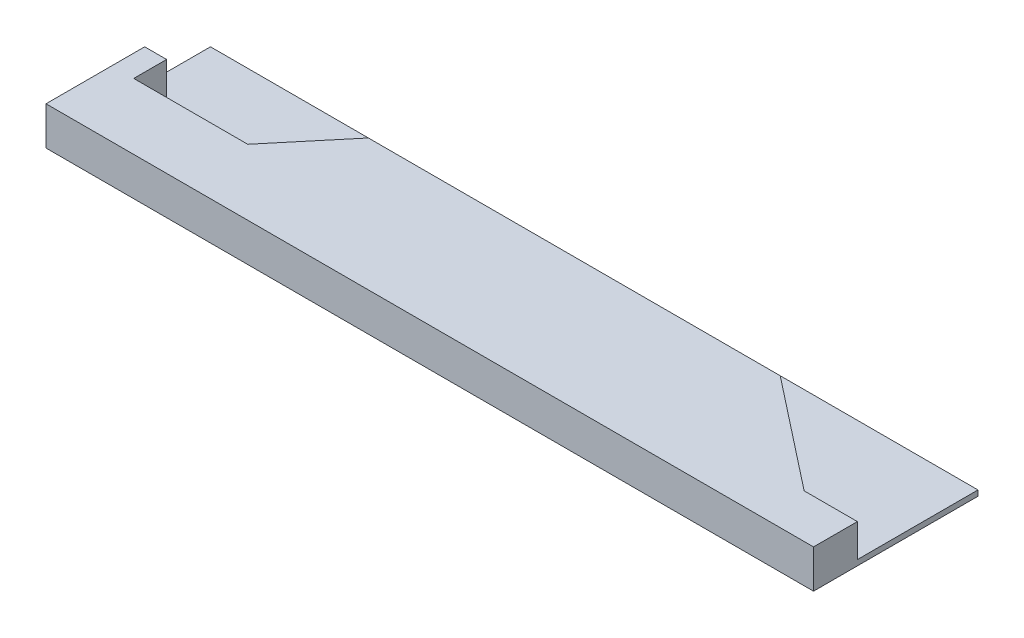
SolidWorks part; units mm, degrees
ref_plane "Front Plane" through (0, 0, 0) normal (0, 0, 1) x (1, 0, 0)
ref_plane "Top Plane" through (0, 0, 0) normal (0, 1, 0) x (1, 0, 0)
ref_plane "Right Plane" through (0, 0, 0) normal (1, 0, 0) x (0, 0, -1)
sketch "Sketch1" plane through (0, 0, 0) normal (0, 1, 0) x (1, 0, 0)
  line L0 (0, 19.05) -> (0, 57.15)
  line L1 (0, 0) -> (57.15, 0)
  line L2 (0, 0) -> (0, 19.05)
  line L3 (0, 19.05) -> (57.15, 19.05)
  line L4 (57.15, 0) -> (57.15, 19.05)
  line L5 (0, 57.15) -> (88.9, 57.15)
  line L6 (88.9, 57.15) -> (57.15, 19.05)
  line L7 (88.9, 57.15) -> (342.9, 57.15)
  line L8 (342.9, 57.15) -> (431.8, -12.7)
  line L9 (342.9, 57.15) -> (88.9, 57.15)
  line L10 (342.9, 57.15) -> (342.9, 38.1)
  line L11 (342.9, 38.1) -> (88.9, 38.1)
  line L12 (88.9, 57.15) -> (88.9, 38.1)
  line L13 (342.9, 57.15) -> (431.8, 57.15)
  line L14 (342.9, 57.15) -> (342.9, -12.7)
  line L15 (342.9, -12.7) -> (431.8, -12.7)
  line L16 (431.8, 57.15) -> (431.8, -12.7)
  line L17 (431.8, -12.7) -> (420.0305, -27.6794)
  line L18 (420.0305, -27.6794) -> (336.3113, 38.1)
  line L19 (57.15, 19.05) -> (73.025, 38.1)
  line L20 (57.15, 19.05) -> (71.1524, 6.1336)
  line L21 (71.1524, 6.1336) -> (103.8794, 45.3805)
  line L22 (57.15, 0) -> (66.0378, 0)
  line L23 (88.9, 57.15) -> (103.8794, 45.3805)
  line L24 (73.025, 38.1) -> (87.6596, 25.9045)
  line L25 (71.1524, 6.1336) -> (64.1512, -2.2625)
extrude "Boss-Extrude1" add sketch "Sketch1" along normal blind 19.05
sketch "Sketch2" plane through (0, 0, 0) normal (0, 0, 1) x (1, 0, 0)
  line L0 (0, 9.525) -> (8.89, 9.525)
  line L1 (0, 19.05) -> (0, 0) construction
  line L2 (0, 9.525) -> (56.515, 9.525)
  circle A0 centre (8.89, 9.525) radius 3.9688
  circle A1 centre (56.515, 9.525) radius 3.9687
extrude "Cut-Extrude1" cut sketch "Sketch2" against normal blind 19.05
sketch "Sketch3" plane through (0, 0, 0) normal (0, -1, 0) x (1, 0, 0)
  line L0 (0, -19.05) -> (0, 0)
  line L1 (0, 0) -> (66.0378, 0)
  line L2 (66.0378, 0) -> (97.8084, -38.1)
  line L3 (97.8084, -38.1) -> (336.3113, -38.1)
  line L4 (336.3113, -38.1) -> (400.9659, 12.7)
  line L5 (400.9659, 12.7) -> (431.8, 12.7)
  line L6 (431.8, 12.7) -> (342.9, -57.15)
  line L7 (342.9, -57.15) -> (88.9, -57.15)
  line L8 (88.9, -57.15) -> (57.15, -19.05)
  line L9 (57.15, -19.05) -> (0, -19.05)
  line L10 (0, -19.05) -> (-12.7, -19.05)
  line L11 (-12.7, -19.05) -> (-12.7, -114.3)
  line L12 (431.8, 12.7) -> (431.8, 38.1)
  line L13 (431.8, 38.1) -> (444.5, 38.1)
  line L15 (-12.7, -114.3) -> (444.5, -114.3)
  line L16 (-12.7, -114.3) -> (-12.7, 38.1)
  line L17 (-12.7, 38.1) -> (444.5, 38.1)
  line L18 (444.5, -114.3) -> (444.5, 38.1)
extrude "Boss-Extrude3" add sketch "Sketch3" along normal blind 19.05 separate body contours L15 L18 L13 L12 L7 L6 L5 L4 L10 L11 | L17 L16 L10 L3 L2 L1 L0 L9 L8 L12
sketch "Sketch4" plane through (0, 0, 0) normal (0, 1, 0) x (1, 0, 0)
  line L1 (444.5, 114.3) -> (-12.7, 114.3)
  line L2 (444.5, 114.3) -> (444.5, -38.1)
  line L3 (444.5, -38.1) -> (-12.7, -38.1)
  line L4 (-12.7, 114.3) -> (-12.7, -38.1)
extrude "Cut-Extrude2" cut sketch "Sketch4" along normal blind 25.4
sketch "Sketch5" plane through (0, -19.05, 0) normal (0, -1, 0) x (1, 0, 0)
  line L0 (0, -19.05) -> (-12.7, -19.05)
  line L1 (-12.7, 38.1) -> (-12.7, -114.3) construction
  line L2 (-12.7, -19.05) -> (57.15, -19.05)
  line L3 (57.15, -19.05) -> (88.9, -57.15)
  line L4 (88.9, -57.15) -> (342.9, -57.15)
  line L5 (342.9, -57.15) -> (431.8, 12.7)
  line L6 (431.8, 12.7) -> (431.8, 38.1)
  line L7 (-12.7, 38.1) -> (444.5, 38.1) construction
  line L8 (431.8, 38.1) -> (-12.7, 38.1)
  line L9 (-12.7, 38.1) -> (-12.7, -19.05)
  line M1 (444.5, 38.1) -> (-12.7, 38.1)
  line M2 (-12.7, 38.1) -> (-12.7, -114.3)
  line M3 (-12.7, -114.3) -> (444.5, -114.3)
  line M4 (444.5, -114.3) -> (444.5, 38.1)
  line M6 (431.8, 12.7) -> (342.9, -57.15)
  line M7 (342.9, -57.15) -> (88.9, -57.15)
  line M8 (88.9, -57.15) -> (57.15, -19.05)
  line M9 (57.15, -19.05) -> (0, -19.05)
extrude "Cut-Extrude3" cut sketch "Sketch5" against normal blind 25.4 contours L6 L0 M6 M7 M8 M9 M2 M3 M4 M1
sketch "Sketch6" plane through (0, -19.05, 0) normal (0, -1, 0) x (1, 0, 0)
  line L0 (336.3113, -38.1) -> (336.3113, -57.15)
  line L2 (336.3113, -57.15) -> (-12.7, -57.15)
  line L3 (336.3113, -57.15) -> (336.3113, 38.1)
  line L4 (336.3113, 38.1) -> (-12.7, 38.1)
  line L5 (-12.7, -57.15) -> (-12.7, 38.1)
  line L6 (336.3113, -57.15) -> (431.8, -57.15)
  line L7 (336.3113, -57.15) -> (336.3113, 38.1)
  line L8 (336.3113, 38.1) -> (431.8, 38.1)
  line L9 (431.8, -57.15) -> (431.8, 38.1)
  line M1 (400.9659, 12.7) -> (431.8, 12.7)
  line M2 (431.8, 12.7) -> (431.8, 38.1)
  line M3 (431.8, 38.1) -> (-12.7, 38.1)
  line M4 (-12.7, 38.1) -> (-12.7, -19.05)
  line M5 (-12.7, -19.05) -> (0, -19.05)
  line M6 (0, -19.05) -> (0, 0)
  line M7 (0, 0) -> (66.0378, 0)
  line M8 (66.0378, 0) -> (97.8084, -38.1)
  line M9 (97.8084, -38.1) -> (336.3113, -38.1)
  line M10 (336.3113, -38.1) -> (400.9659, 12.7)
extrude "Boss-Extrude4" add sketch "Sketch6" along normal blind 3.175 contours L6 L9 L0 M1 M10 | L5 L2 L0 M9 M8 M7 M6 M5 | L3 M9 M3 M4 M5 M6 M7 M8 | L3 M10 M1 M2 M3
